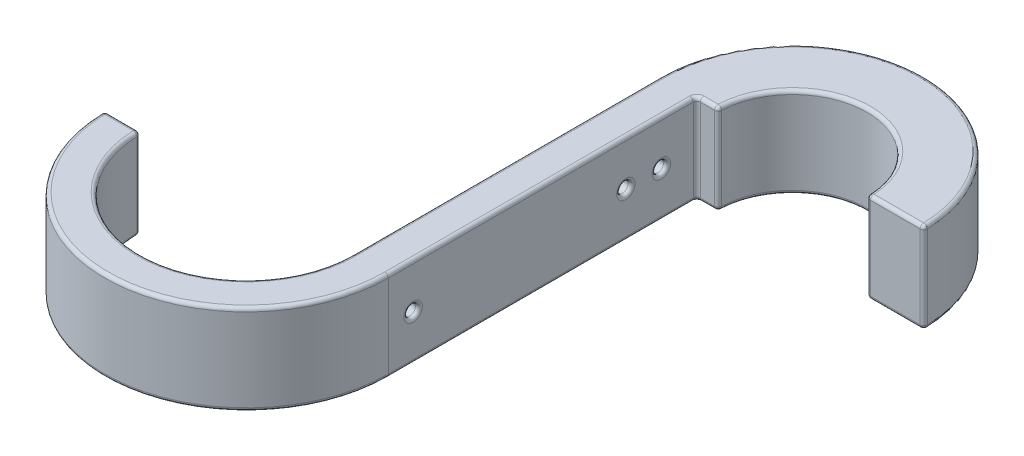
SolidWorks part; units mm, degrees
ref_plane "Front Plane" through (0, 0, 0) normal (0, 0, 1) x (1, 0, 0)
ref_plane "Top Plane" through (0, 0, 0) normal (0, 1, 0) x (1, 0, 0)
ref_plane "Right Plane" through (0, 0, 0) normal (1, 0, 0) x (0, 0, -1)
sketch "Sketch1" plane through (0, 0, 0) normal (0, 1, 0) x (1, 0, 0)
  line L0 (42, 0) -> (58, 0)
  line L1 (0, 0) -> (-6, 0)
  line L2 (-16, 0) -> (-16, -87)
  line L3 (-6, 0) -> (-6, -87)
  line L4 (-86, -87) -> (-76, -87)
  circle A0 centre (21, 0) radius 21 construction
  arc A1 (58, 0) -> (-16, 0) centre (21, 0) ccw
  circle A2 centre (-46, -87) radius 30 construction
  arc A3 (-16, -87) -> (-76, -87) centre (-46, -87) cw
  arc A4 (-6, -87) -> (-86, -87) centre (-46, -87) cw
  arc A5 (0, 0) -> (42, 0) centre (21, 0) cw
  point P3 (-141.3924, 41.1061)
  dimension "D1" = 10
  dimension "D3" = 37
  dimension "D4" = 87
  dimension "D5" = 21
  dimension "D2" = 6
extrude "Boss-Extrude1" add sketch "Sketch1" along normal blind 25.4 contours L3 A4 L4 A3 L2 A1 L0 A5 L1
sketch "Sketch3" plane through (-6, 0, 0) normal (1, 0, 0) x (0, 0, -1)
  circle A0 centre (-20, 12.7) radius 1.6
  circle A1 centre (-10, 12.7) radius 1.6
  circle A2 centre (-80, 12.7) radius 1.6
extrude "Cut-Extrude2" cut sketch "Sketch3" against normal through all
fillet "Fillet1" radius 1 30 edges at (0, 12.7, 0) (42, 12.7, 0) (58, 12.7, 0) (-16, 12.7, 18.4) (-16, 12.7, 8.4) (-16, 12.7, 78.4) (-76, 12.7, 87) (-86, 12.7, 87) (-6, 12.7, 0) (-6, 12.7, 18.4) (-6, 12.7, 8.4) (-6, 12.7, 78.4) (-6, 25.4, 43.5) (-46, 25.4, 127) (-81, 25.4, 87) (-46, 25.4, 117) (-16, 25.4, 43.5) (21, 25.4, -37) (50, 25.4, 0) (21, 25.4, -21) (-3, 25.4, 0) (21, 0, -21) (50, 0, 0) (21, 0, -37) (-16, 0, 43.5) (-46, 0, 117) (-81, 0, 87) (-46, 0, 127) (-6, 0, 43.5) (-3, 0, 0)
